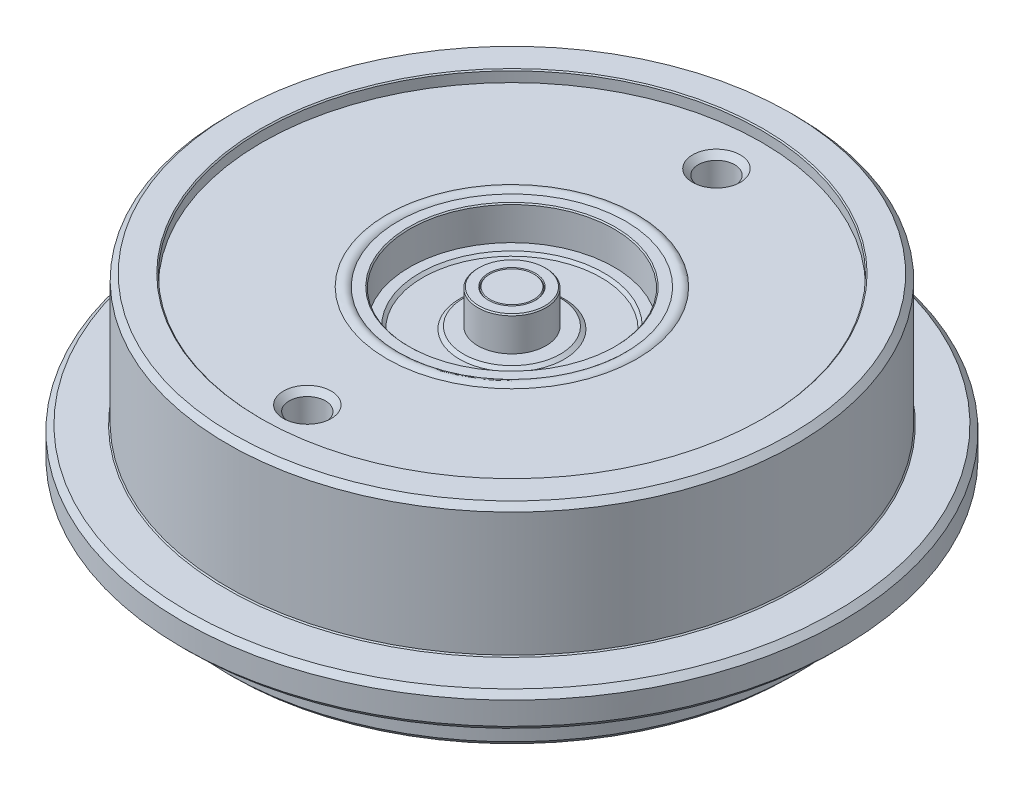
SolidWorks part; units mm, degrees
material "7079 Alloy"
ref_plane "Front Plane" through (0, 0, 0) normal (0, 0, 1) x (1, 0, 0)
ref_plane "Top Plane" through (0, 0, 0) normal (0, 1, 0) x (1, 0, 0)
ref_plane "Right Plane" through (0, 0, 0) normal (1, 0, 0) x (0, 0, -1)
sketch "Sketch1" plane through (0, 0, 0) normal (0, 0, 1) x (1, 0, 0)
  line L0 (840.9424, 295.3889) -> (840.0515, 295.3889)
  line L1 (834.0099, 298.3889) -> (834.9424, 298.3889)
  line L2 (841.9424, 280.8889) -> (856.9424, 280.8889)
  line L3 (831.9424, 300.6704) -> (831.9424, 289.6846) construction
  line L4 (831.9424, 298.3889) -> (833.8727, 298.3889)
  line L5 (834.9424, 298.3889) -> (834.9424, 295.3889)
  line L6 (831.9424, 298.3889) -> (831.9424, 270.8889)
  line L7 (833.8727, 298.3889) -> (833.9424, 298.3203)
  line L8 (831.9424, 270.8889) -> (834.9424, 270.8889)
  line L9 (834.9424, 270.8889) -> (834.9424, 281.3889)
  line L10 (833.9424, 298.3203) -> (834.0099, 298.3889)
  line L11 (836.2077, 295.3889) -> (836.5487, 295.1639)
  line L12 (836.5487, 295.1639) -> (839.7951, 295.1639)
  line L13 (840.9424, 298.3889) -> (841.9424, 298.3889)
  line L14 (840.0515, 295.3889) -> (839.7951, 295.1639)
  line L15 (835.8305, 282.3889) -> (840.9424, 282.3889) construction
  line L16 (835.8305, 282.3889) -> (835.8305, 288.3889) construction
  line L17 (856.9424, 299.3889) -> (853.9424, 299.3889)
  line L18 (835.8305, 288.3889) -> (840.9424, 288.3889) construction
  line L19 (842.9424, 298.3889) -> (853.9424, 298.3889)
  line L20 (836.2077, 295.3889) -> (834.9424, 295.3889)
  line L21 (840.9424, 282.3889) -> (840.9424, 288.3889) construction
  line L22 (840.9424, 288.3889) -> (839.0782, 288.3889) construction
  line L23 (840.9424, 298.3889) -> (840.9424, 295.3889)
  line L24 (836.2976, 281.3889) -> (834.9424, 281.3889)
  line L25 (840.9424, 289.3889) -> (839.0782, 289.3889) construction
  line L26 (839.0782, 288.3889) -> (839.0782, 289.3889) construction
  line L27 (840.9424, 289.3889) -> (835.6621, 289.3889) construction
  line L28 (853.9424, 299.3889) -> (853.9424, 298.3889)
  line L29 (840.9424, 289.3889) -> (840.9424, 295.3889) construction
  line L33 (840.9424, 295.3889) -> (835.6621, 295.3889) construction
  line L34 (856.9424, 284.8889) -> (856.9424, 280.8889)
  line L35 (860.9424, 284.8889) -> (856.9424, 284.8889)
  line L36 (860.9424, 284.8889) -> (860.9424, 287.8889)
  line L37 (835.6621, 289.3889) -> (835.6621, 295.3889) construction
  line L39 (860.9424, 287.8889) -> (856.9424, 287.8889)
  line L40 (856.9424, 287.8889) -> (856.9424, 299.3889)
  line L46 (841.4424, 281.3889) -> (841.9424, 280.8889)
  line L48 (836.2976, 281.3889) -> (836.5487, 281.62)
  line L49 (836.5487, 281.62) -> (839.7951, 281.62)
  line L50 (839.7951, 281.62) -> (840.0078, 281.3889)
  line L51 (840.0078, 281.3889) -> (841.4424, 281.3889)
  arc A0 (841.9424, 298.3889) -> (842.9424, 298.3889) centre (842.4424, 297.8889) cw
  dimension "D1" = 4
  dimension "D3" = 17.5
  dimension "D5" = 29
  dimension "D6" = 3
  dimension "D7" = 3
  dimension "D8" = 10
  dimension "D9" = 1
  dimension "D15" = 9
  dimension "D18" = 22
  dimension "D24" = 6
  dimension "D25" = 1
  dimension "D26" = 6
  dimension "D27" = 3
  dimension "D28" = 3
  dimension "D30" = 3
  dimension "D31" = 25
  dimension "D34" = 25
revolve "Revolve4" add sketch "Sketch1" angle 360 about L3
sketch "Sketch2" plane through (0, 298.3889, 0) normal (0, 1, 0) x (-1, 0, 0)
  circle A0 centre (-831.9391, 18) radius 1.6
  circle A1 centre (-831.9391, -18) radius 1.6
  circle A2 centre (-831.9424, 0) radius 9 construction
  dimension "D1" = 18
  dimension "D2" = 18
  dimension "D3" = 3.2
  dimension "D4" = 3.2
sketch "Sketch4" plane through (0, 280.8889, 0) normal (0, -1, 0) x (1, 0, 0)
  line L0 (831.9424, 0) -> (862.8935, 0) construction
  circle A0 centre (831.9424, 0) radius 21 construction
  circle A1 centre (852.9424, 0) radius 1.6
  circle A2 centre (821.4424, -18.1865) radius 1.6
  circle A3 centre (821.4424, 18.1865) radius 1.6
  dimension "D1" = 42
  dimension "D2" = 3.2
extrude "Cut-Extrude1" cut sketch "Sketch2" against normal blind 6
extrude "Cut-Extrude2" cut sketch "Sketch4" against normal blind 6
sketch "Sketch5" plane through (0, 292.3889, 0) normal (0, 1, 0) x (-1, 0, 0)
  circle A2 centre (-831.9391, 18) radius 1.6
  circle A3 centre (-831.9391, 18) radius 1.6
  circle A5 centre (-831.9391, -18) radius 1.6
  circle A6 centre (-831.9391, -18) radius 1.6
  dimension "D1" = 0
  dimension "D2" = 0
extrude "Cut-Extrude3" cut sketch "Sketch5" against normal blind 2 draft 55
sketch "Sketch6" plane through (0, 286.8889, 0) normal (0, -1, 0) x (1, 0, 0)
  circle A2 centre (821.4424, 18.1865) radius 1.6
  circle A3 centre (821.4424, 18.1865) radius 1.6
  circle A5 centre (821.4424, -18.1865) radius 1.6
  circle A6 centre (821.4424, -18.1865) radius 1.6
  circle A8 centre (852.9424, 0) radius 1.6
  circle A9 centre (852.9424, 0) radius 1.6
  dimension "D1" = 0
  dimension "D2" = 0
  dimension "D3" = 0
extrude "Cut-Extrude4" cut sketch "Sketch6" against normal blind 2 draft 55
chamfer "Chamfer3" distance 0.1 angle 45 5 edges at (831.9424, 298.3889, 9) (831.9424, 299.3889, 22) (831.9424, 298.3889, 3) (831.9424, 284.8889, 25) (831.9424, 287.8889, 25)
chamfer "Chamfer1" distance 0.5 angle 45 10 edges at (831.9424, 284.8889, 29) (831.9424, 287.8889, 29) (831.9424, 299.3889, 25) (831.9391, 298.3889, -16.4) (831.9391, 298.3889, 19.6) (821.4424, 280.8889, -19.7865) (852.9424, 280.8889, -1.6) (821.4424, 280.8889, 16.5865) (831.9424, 270.8889, 3) (831.9424, 280.8889, 25)
